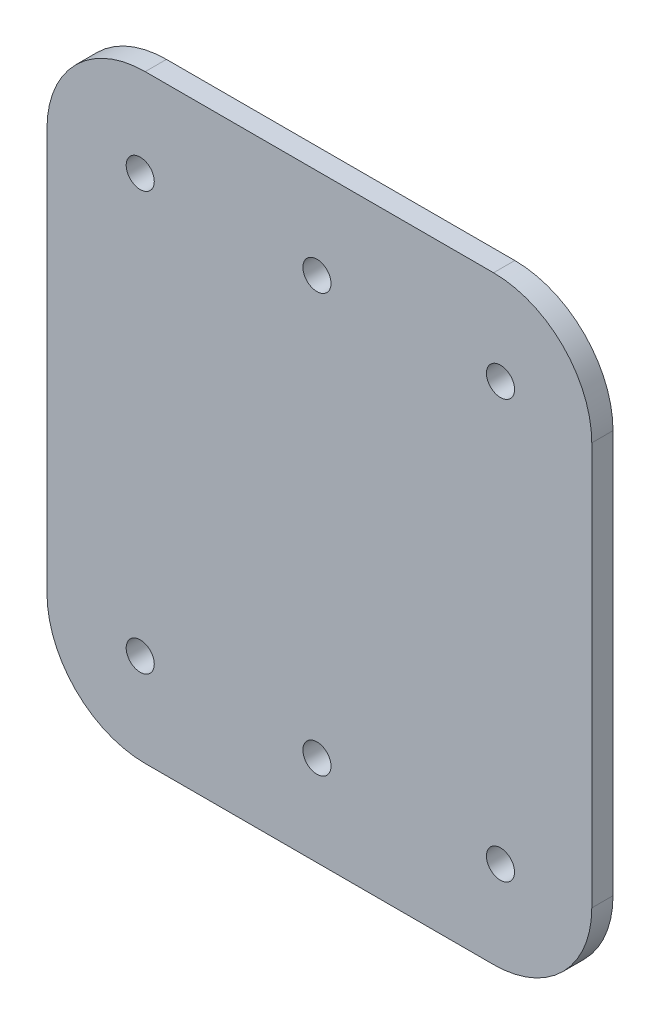
SolidWorks part; units mm, degrees
material "ABS PC"
ref_plane "X-Y Datum" through (0, 0, 0) normal (0, 0, 1) x (1, 0, 0)
ref_plane "X-Z Datum" through (0, 0, 0) normal (0, 1, 0) x (1, 0, 0)
ref_plane "Y-Z Datum" through (0, 0, 0) normal (1, 0, 0) x (0, 0, -1)
sketch "Sketch1" plane through (0, 0, 0) normal (0, 0, 1) x (1, 0, 0)
  line L10 (11.3538, 133.985) -> (11.3538, 73.787)
  line L11 (78.105, 148.6662) -> (26.035, 148.6662)
  line L18 (92.7862, 73.787) -> (92.7862, 133.985)
  line L19 (26.035, 59.1058) -> (78.105, 59.1058)
  arc A8 (11.3538, 73.787) -> (26.035, 59.1058) centre (26.035, 73.787) ccw
  arc A9 (26.035, 148.6662) -> (11.3538, 133.985) centre (26.035, 133.985) ccw
  arc A12 (78.105, 59.1058) -> (92.7862, 73.787) centre (78.105, 73.787) ccw
  circle A13 centre (25.292, 135.128) radius 2.1
  arc A15 (92.7862, 133.985) -> (78.105, 148.6662) centre (78.105, 133.985) ccw
  circle A16 centre (51.708, 135.128) radius 2.1
  circle A17 centre (79.14, 135.128) radius 2.1
  circle A18 centre (79.14, 72.644) radius 2.1
  circle A19 centre (51.708, 72.644) radius 2.1
  circle A20 centre (25.292, 72.644) radius 2.1
extrude "Boss-Extrude1" add sketch "Sketch1" along normal blind 3.175
